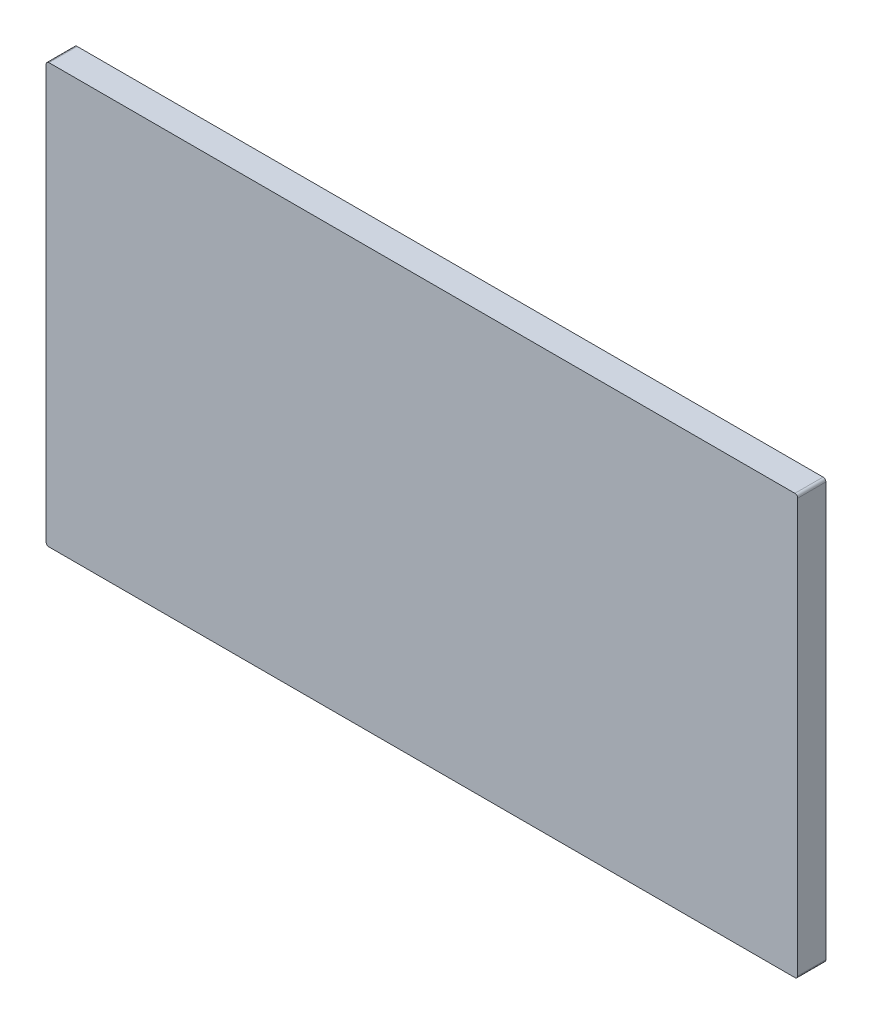
SolidWorks part; units mm, degrees
ref_plane "Front Plane" through (0, 0, 0) normal (0, 0, 1) x (1, 0, 0)
ref_plane "Top Plane" through (0, 0, 0) normal (0, 1, 0) x (1, 0, 0)
ref_plane "Right Plane" through (0, 0, 0) normal (1, 0, 0) x (0, 0, -1)
sketch "Sketch1" plane through (0, 0, 0) normal (0, 0, 1) x (1, 0, 0)
  line L1 (-13.35, 7.45) -> (13.35, 7.45)
  line L2 (-13.35, 7.45) -> (-13.35, -7.45)
  line L3 (-13.35, -7.45) -> (13.35, -7.45)
  line L4 (13.35, 7.45) -> (13.35, -7.45)
  line L5 (-13.35, 7.45) -> (13.35, -7.45) construction
  line L6 (-13.35, -7.45) -> (13.35, 7.45) construction
  point P0 (0, 0)
  dimension "D1" = 26.7
  dimension "D2" = 14.9
extrude "Boss-Extrude1" add sketch "Sketch1" along normal blind 1
fillet "Fillet1" radius 0.1 4 edges at (-13.35, 7.45, 0.5) (-13.35, -7.45, 0.5) (13.35, -7.45, 0.5) (13.35, 7.45, 0.5)
sketch "Sketch2" plane through (0, 0, 0) normal (0, 0, -1) x (-1, 0, 0)
  line L0 (-13.35, -7.35) -> (-13.35, 7.35) construction
  line L1 (-10.872, 5.35) -> (10.872, 5.35)
  line L2 (-10.872, 5.35) -> (-10.872, -5.514)
  line L3 (-10.872, -5.514) -> (10.872, -5.514)
  line L4 (10.872, 5.35) -> (10.872, -5.514)
  line L5 (13.35, 7.35) -> (13.35, -7.35) construction
  line L6 (-13.25, 7.45) -> (13.25, 7.45) construction
  dimension "D1" = 2.478
  dimension "D2" = 2.478
  dimension "D3" = 2.1
  dimension "D4" = 10.864
extrude "Cut-Extrude1" cut sketch "Sketch2" against normal blind 0.1
